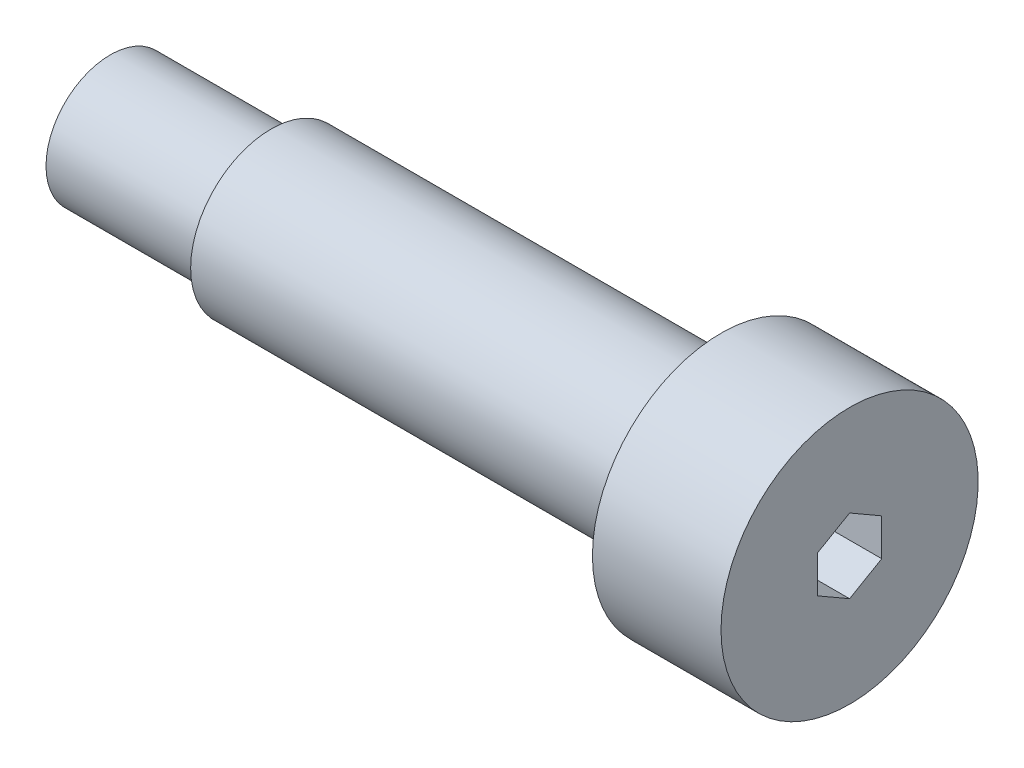
SolidWorks part; units mm, degrees
ref_plane "Front Plane" through (0, 0, 0) normal (0, 0, 1) x (1, 0, 0)
ref_plane "Top Plane" through (0, 0, 0) normal (0, 1, 0) x (1, 0, 0)
ref_plane "Right Plane" through (0, 0, 0) normal (1, 0, 0) x (0, 0, -1)
sketch "Sketch1" plane through (0, 0, 0) normal (0, 0, 1) x (1, 0, 0)
  line L0 (0, 0) -> (104.2442, 0) construction
  line L1 (18, 0) -> (18, 4)
  line L2 (18, 4) -> (14, 4)
  line L3 (14, 4) -> (14, 2.5)
  line L4 (14, 2.5) -> (0, 2.5)
  line L5 (0, 2.5) -> (0, 2)
  line L6 (0, 2) -> (-5, 2)
  line L7 (-5, 2) -> (-5, 0)
  line L8 (-5, 0) -> (18, 0)
  dimension "D_THREAD" = 4
  dimension "L_THREAD" = 5
  dimension "D_SHANK" = 5
  dimension "L_SHANK" = 14
  dimension "L_HEAD" = 4
  dimension "D_HEAD" = 8
revolve "Revolve1" add sketch "Sketch1" angle 360 about L0
cosmetic thread "Cosmetic Thread1" parameters "D2"=3.22
sketch "Sketch2" plane through (18, 0, 0) normal (1, 0, 0) x (0, 0, -1)
  line L1 (0, 1.1547) -> (-1, 0.5774)
  line L2 (-1, 0.5774) -> (-1, -0.5774)
  line L3 (-1, -0.5774) -> (0, -1.1547)
  line L4 (0, -1.1547) -> (1, -0.5774)
  line L5 (1, -0.5774) -> (1, 0.5774)
  line L6 (1, 0.5774) -> (0, 1.1547)
  circle A0 centre (0, 0) radius 1 construction
  dimension "D1" = 2
extrude "Cut-Extrude1" cut sketch "Sketch2" against normal blind 2
